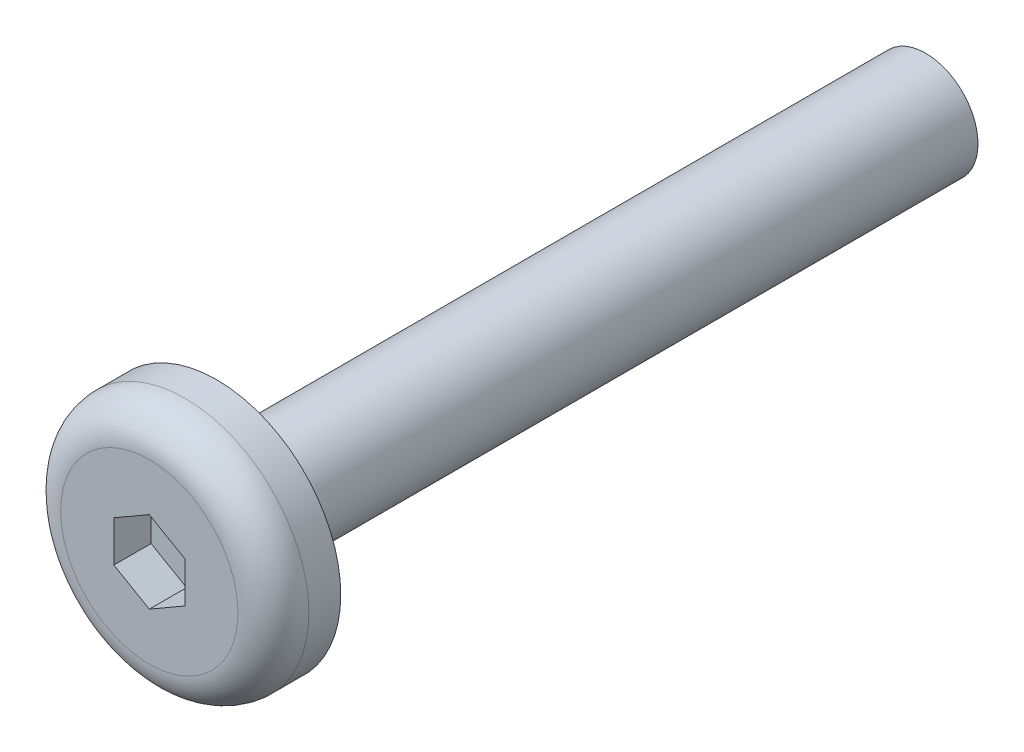
SolidWorks part; units mm, degrees
material "Chrome Stainless Steel"
ref_plane "Front Plane" through (0, 0, 0) normal (0, 0, 1) x (1, 0, 0)
ref_plane "Top Plane" through (0, 0, 0) normal (0, 1, 0) x (1, 0, 0)
ref_plane "Right Plane" through (0, 0, 0) normal (1, 0, 0) x (0, 0, -1)
sketch "Sketch1" plane through (0, 0, 0) normal (1, 0, 0) x (0, 0, -1)
  line L0 (1.9, 1.475) -> (1.9, 3.5)
  line L1 (0, 0) -> (21.9, 0)
  line L3 (1.9, 1.475) -> (21.9, 1.475)
  line L4 (21.9, 0) -> (21.9, 1.475)
  line L5 (1.9, 3.5) -> (0, 3.5)
  line L6 (0, 3.5) -> (0, 0)
  dimension "D1" = 20
  dimension "D2" = 1.475
  dimension "D3" = 3.5
  dimension "D4" = 1.9
revolve "Revolve1" add sketch "Sketch1" angle 360 about L1
fillet "Fillet1" radius 1 1 edges at (3.5, 0, 0)
sketch "Sketch2" plane through (0, 0, 0) normal (0, 0, 1) x (1, 0, 0)
  line L1 (0, 1.1547) -> (-1, 0.5774)
  line L2 (-1, 0.5774) -> (-1, -0.5774)
  line L3 (-1, -0.5774) -> (0, -1.1547)
  line L4 (0, -1.1547) -> (1, -0.5774)
  line L5 (1, -0.5774) -> (1, 0.5774)
  line L6 (1, 0.5774) -> (0, 1.1547)
  circle A0 centre (0, 0) radius 1 construction
  dimension "D1" = 2
extrude "Cut-Extrude1" cut sketch "Sketch2" against normal blind 1.05
